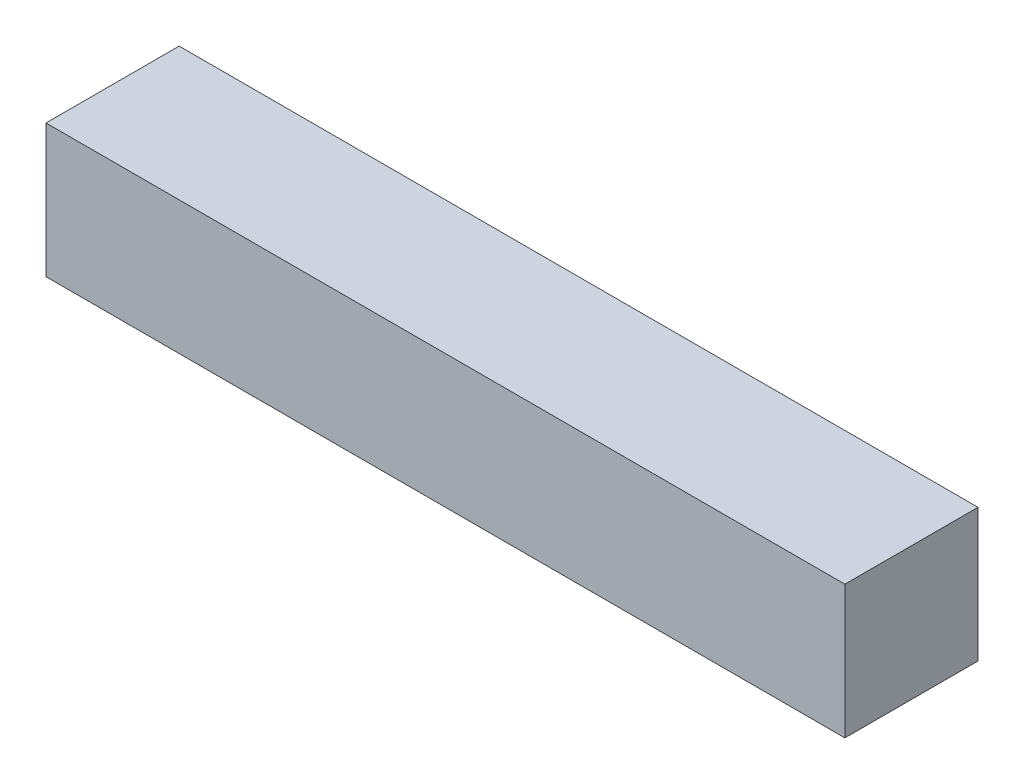
SolidWorks part; units mm, degrees
ref_plane "前视基准面" through (0, 0, 0) normal (0, 0, 1) x (1, 0, 0)
ref_plane "上视基准面" through (0, 0, 0) normal (0, 1, 0) x (1, 0, 0)
ref_plane "右视基准面" through (0, 0, 0) normal (1, 0, 0) x (0, 0, -1)
other "Configuration Table"
sketch "草图1" plane through (0, 0, 0) normal (0, 0, 1) x (1, 0, 0)
  line L1 (-210, -35) -> (210, -35)
  line L2 (-210, -35) -> (-210, 35)
  line L3 (-210, 35) -> (210, 35)
  line L4 (210, -35) -> (210, 35)
  line L5 (-210, -35) -> (210, 35) construction
  line L6 (-210, 35) -> (210, -35) construction
  point P0 (0, 0)
extrude "凸台-拉伸1" add sketch "草图1" along normal blind 70
